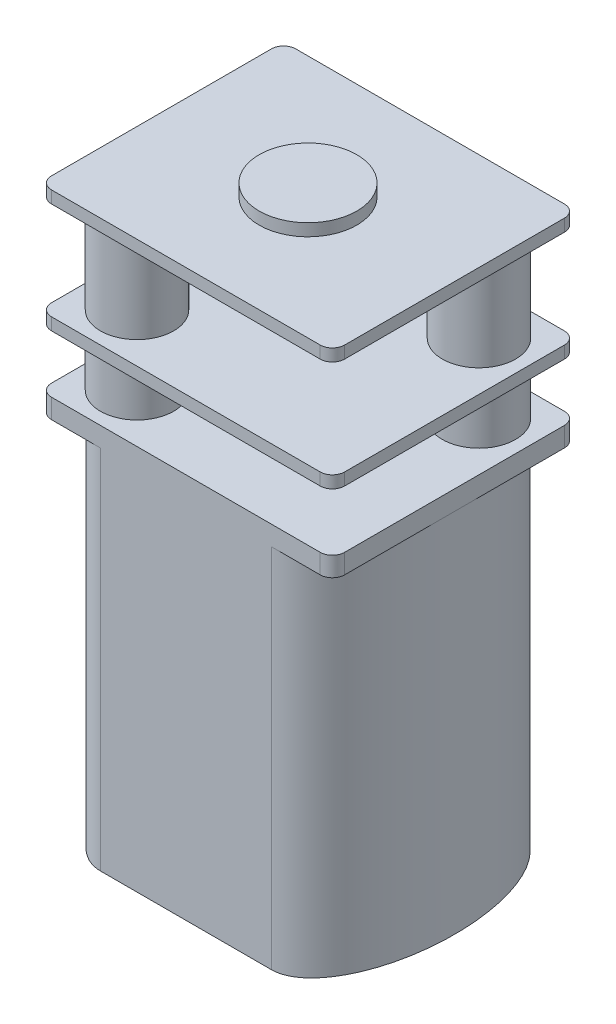
SolidWorks part; units mm, degrees
ref_plane "Front Plane" through (0, 0, 0) normal (0, 0, 1) x (1, 0, 0)
ref_plane "Top Plane" through (0, 0, 0) normal (0, 1, 0) x (1, 0, 0)
ref_plane "Right Plane" through (0, 0, 0) normal (1, 0, 0) x (0, 0, -1)
sketch "Sketch1" plane through (0, 0, 0) normal (0, 1, 0) x (1, 0, 0)
  line L1 (-3.5, -5) -> (3.5, -5)
  line L2 (-3.5, -5) -> (-3.5, 5)
  line L3 (-3.5, 5) -> (3.5, 5)
  line L4 (3.5, -5) -> (3.5, 5)
  line L5 (-3.5, -5) -> (3.5, 5) construction
  line L6 (-3.5, 5) -> (3.5, -5) construction
  ellipse E1 centre (-3.5, 0) end of major axis (-3.5, 5) minor radius 2.5026 (-3.5, 5) -> (-3.5, -5) ccw
  ellipse E2 centre (3.5, 0) end of major axis (3.5, 5) minor radius 2.5005 (3.5, -5) -> (3.5, 5) ccw
  point P0 (0, 0)
  dimension "D1" = 7
  dimension "D2" = 10
extrude "Boss-Extrude1" add sketch "Sketch1" along normal blind 15 contours L2 E1 | L1 L4 L3 L2 | L4 E2
sketch "Sketch2" plane through (0, 15, 0) normal (0, 1, 0) x (1, 0, 0)
  line L1 (-5.5, -5) -> (5.5, -5)
  line L2 (-6, -4.5) -> (-6, 4.5)
  line L3 (-5.5, 5) -> (5.5, 5)
  line L4 (6, -4.5) -> (6, 4.5)
  line L5 (-6, -5) -> (6, 5) construction
  line L6 (-6, 5) -> (6, -5) construction
  arc A0 (5.5, 5) -> (6, 4.5) centre (5.5, 4.5) cw
  arc A1 (6, -4.5) -> (5.5, -5) centre (5.5, -4.5) cw
  arc A2 (-5.5, -5) -> (-6, -4.5) centre (-5.5, -4.5) cw
  arc A3 (-6, 4.5) -> (-5.5, 5) centre (-5.5, 4.5) cw
  point P0 (0, 0)
  dimension "D3" = 0.5
  dimension "D1" = 12
  dimension "D2" = 10
extrude "Boss-Extrude2" add sketch "Sketch2" along normal blind 0.8
sketch "Sketch3" plane through (0, 15.8, 0) normal (0, 1, 0) x (1, 0, 0)
  line L0 (-6, 4.5) -> (-6, -4.5) construction
  line L1 (6, -4.5) -> (6, 4.5) construction
  line L2 (-5.5, -5) -> (5.5, -5) construction
  line L3 (5.5, 5) -> (-5.5, 5) construction
  circle A0 centre (4, 3) radius 1.5
  circle A1 centre (-4, -3) radius 1.5
  dimension "D1" = 3
  dimension "D2" = 3
  dimension "D3" = 2
  dimension "D4" = 2
  dimension "D5" = 2
  dimension "D6" = 2
extrude "Boss-Extrude3" add sketch "Sketch3" along normal blind 7.35
ref_plane "Plane1" through (0, 18.15, 0) normal (0, 1, 0) x (1, 0, 0)
sketch "Sketch4" plane through (0, 18.15, 0) normal (0, 1, 0) x (1, 0, 0)
  line L0 (-1.5, 4.5) -> (-1.5, 0.8)
  line L1 (-5.5, -5) -> (5.5, -5)
  line L2 (-6, -4.5) -> (-6, -0.2)
  line L3 (-1, 5) -> (5.5, 5)
  line L4 (6, -4.5) -> (6, 4.5)
  line L5 (-6, -5) -> (6, 5) construction
  line L6 (-6, 5) -> (6, -5) construction
  line L7 (-2, 0.3) -> (-5.5, 0.3)
  arc A0 (5.5, 5) -> (6, 4.5) centre (5.5, 4.5) cw
  arc A1 (6, -4.5) -> (5.5, -5) centre (5.5, -4.5) cw
  arc A2 (-5.5, -5) -> (-6, -4.5) centre (-5.5, -4.5) cw
  arc A3 (-6, -0.2) -> (-5.5, 0.3) centre (-5.5, -0.2) cw
  arc A4 (-2, 0.3) -> (-1.5, 0.8) centre (-2, 0.8) ccw
  arc A5 (-1.5, 4.5) -> (-1, 5) centre (-1, 4.5) cw
  point P0 (0, 0)
  dimension "D3" = 0.5
  dimension "D4" = 0.5
  dimension "D1" = 12
  dimension "D2" = 10
  dimension "D5" = 4.5
  dimension "D6" = 4.7
extrude "Boss-Extrude4" add sketch "Sketch4" along normal blind 0.5
ref_plane "Plane2" through (0, 22.65, 0) normal (0, 1, 0) x (1, 0, 0)
sketch "Sketch6" plane through (0, 22.65, 0) normal (0, 1, 0) x (1, 0, 0)
  line L1 (-5.5, -5) -> (5.5, -5)
  line L2 (-6, -4.5) -> (-6, 4.5)
  line L3 (-5.5, 5) -> (5.5, 5)
  line L4 (6, -4.5) -> (6, 4.5)
  line L5 (-6, -5) -> (6, 5) construction
  line L6 (-6, 5) -> (6, -5) construction
  arc A0 (5.5, 5) -> (6, 4.5) centre (5.5, 4.5) cw
  arc A1 (6, -4.5) -> (5.5, -5) centre (5.5, -4.5) cw
  arc A2 (-5.5, -5) -> (-6, -4.5) centre (-5.5, -4.5) cw
  arc A3 (-6, 4.5) -> (-5.5, 5) centre (-5.5, 4.5) cw
  point P0 (0, 0)
  dimension "D3" = 0.5
  dimension "D1" = 12
  dimension "D2" = 10
extrude "Boss-Extrude5" add sketch "Sketch6" along normal blind 0.5
ref_plane "Plane3" through (0, 23.15, 0) normal (0, 1, 0) x (1, 0, 0)
sketch "Sketch7" plane through (0, 23.15, 0) normal (0, 1, 0) x (1, 0, 0)
  circle A0 centre (0, 0) radius 2
  dimension "D1" = 4
extrude "Boss-Extrude6" add sketch "Sketch7" along normal blind 0.5
sketch "Sketch8" plane through (0, 23.15, 0) normal (0, 1, 0) x (1, 0, 0)
  line L0 (-1.118, 1) -> (1.118, 1)
  circle A0 centre (0, 0) radius 1.5
  dimension "D1" = 3
  dimension "D2" = 1
extrude "Boss-Extrude7" [suppressed] add sketch "Sketch8" along normal blind 10 separate body contours L0 A0
